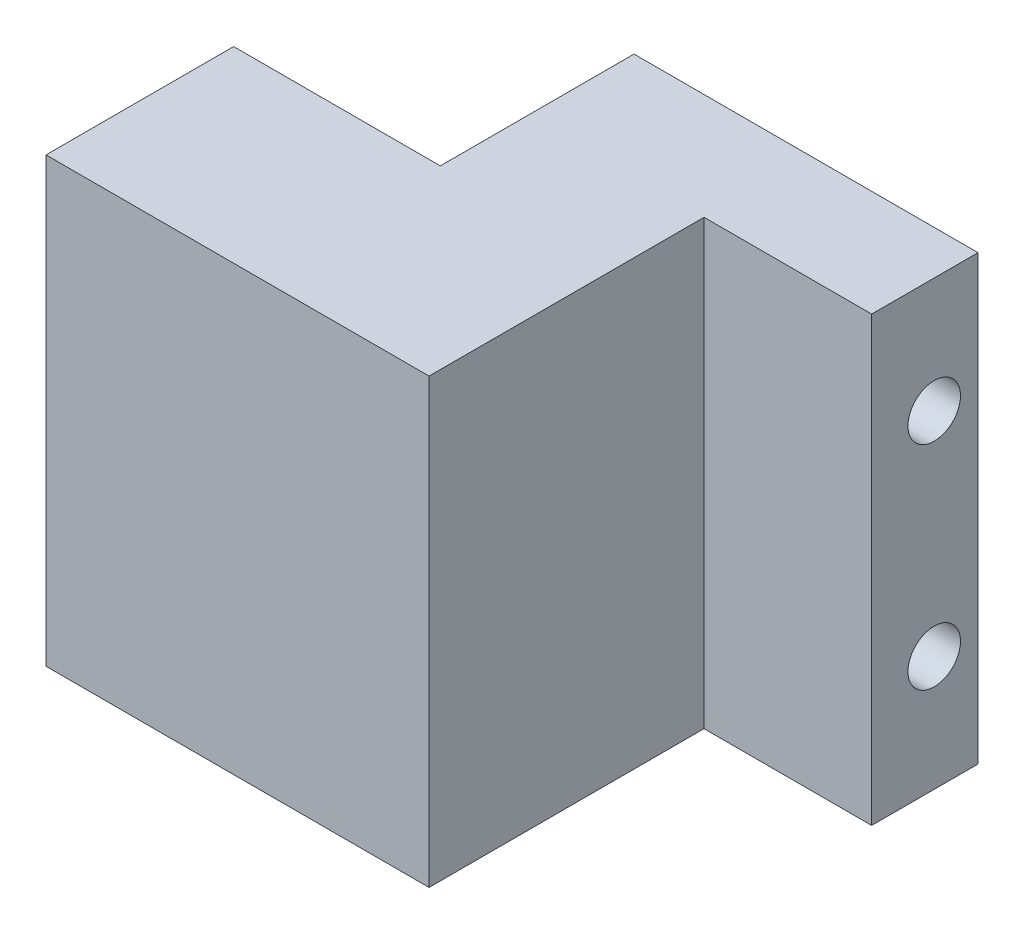
SolidWorks part; units mm, degrees
ref_plane "Front Plane" through (0, 0, 0) normal (0, 0, 1) x (1, 0, 0)
ref_plane "Top Plane" through (0, 0, 0) normal (0, 1, 0) x (1, 0, 0)
ref_plane "Right Plane" through (0, 0, 0) normal (1, 0, 0) x (0, 0, -1)
sketch "Sketch1" plane through (0, 0, 0) normal (0, 1, 0) x (1, 0, 0)
  line L0 (1.0174, 0.48) -> (-26.48, 0.48)
  line L20 (1.0174, 0.48) -> (1.0174, -8.02)
  line L22 (-11.48, -8.02) -> (1.0174, -8.02)
  line L25 (-31.48, -15) -> (-43, -15)
  line L27 (-11.48, -8.02) -> (-12.38, -8.02)
  line L29 (-31.48, -15) -> (-26.48, -15)
  line L30 (-26.48, -15) -> (-26.48, 0.48)
  line L32 (-43, -15) -> (-43, -30)
  line L33 (-43, -30) -> (-12.38, -30)
  line L34 (-12.38, -30) -> (-12.38, -8.02)
  dimension "D1" = 0.9
  dimension "D2" = 5
extrude "Boss-Extrude1" add sketch "Sketch1" along normal blind 35.4
sketch "Sketch2" plane through (-43, 0, 0) normal (-1, 0, 0) x (0, 0, 1)
  line L1 (26.815, 4.925) -> (18.185, 4.925)
  line L2 (26.815, 4.925) -> (26.815, 30.475)
  line L3 (26.815, 30.475) -> (18.185, 30.475)
  line L4 (18.185, 4.925) -> (18.185, 30.475)
  line L5 (26.815, 4.925) -> (18.185, 30.475) construction
  line L6 (26.815, 30.475) -> (18.185, 4.925) construction
  point P4 (25, 17.7)
  dimension "D1" = 25.55
  dimension "D2" = 8.63
extrude "Cut-Extrude1" cut sketch "Sketch2" against normal blind 30
sketch "Sketch3" plane through (1.0174, 0, 0) normal (1, 0, 0) x (0, 0, -1)
  line L0 (0.48, 25.7) -> (0.48, 9.7)
  line L1 (0.48, 35.4) -> (0.48, 0) construction
  line L2 (0.48, 9.2) -> (-3.02, 9.2)
  line L3 (0.48, 17.7) -> (-3.9365, 17.7)
  line L4 (0.48, 26.2) -> (0.48, 9.2)
  circle A2 centre (-3.02, 9.2) radius 2.1
  circle A3 centre (-3.02, 26.2) radius 2.1
  point P5 (0.48, 17.7)
  point P14 (0.48, 17.7)
  dimension "D2" = 4.2
  dimension "D1" = 3.5
  dimension "D3" = 8.5
extrude "Cut-Extrude2" cut sketch "Sketch3" against normal through all
